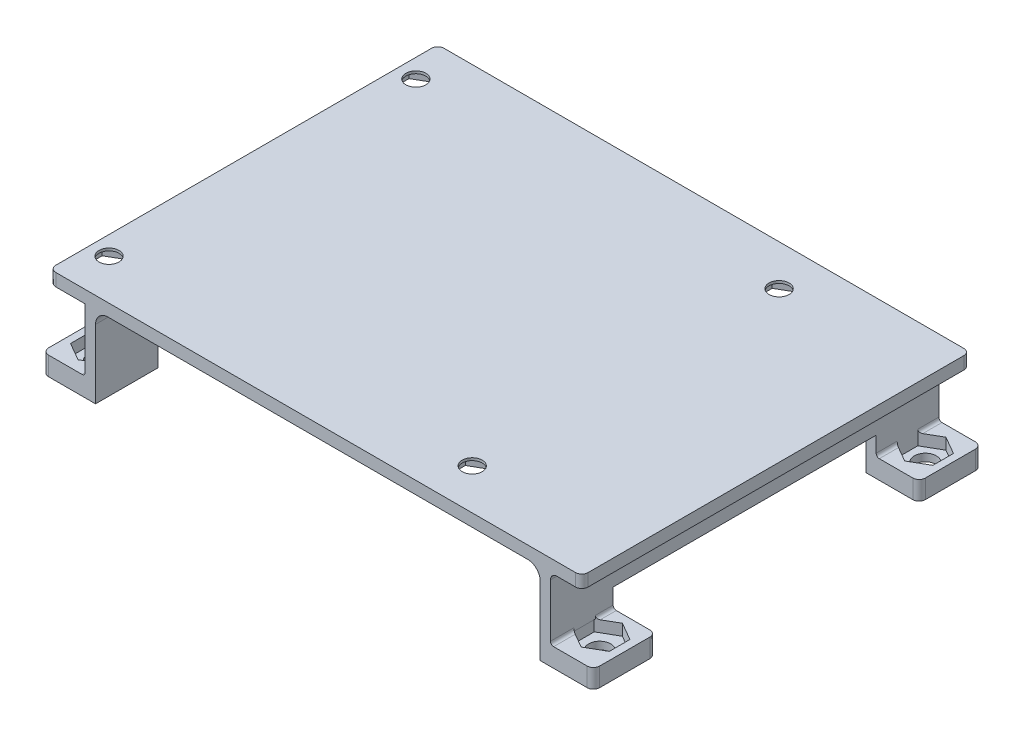
SolidWorks part; units mm, degrees
ref_plane "前基準面" through (0, 0, 0) normal (0, 0, 1) x (1, 0, 0)
ref_plane "上基準面" through (0, 0, 0) normal (0, 1, 0) x (1, 0, 0)
ref_plane "右基準面" through (0, 0, 0) normal (1, 0, 0) x (0, 0, -1)
sketch "草圖1" plane through (0, 0, 0) normal (0, 0, 1) x (1, 0, 0)
  line L0 (-133.4262, 0) -> (6537.8852, 0) construction
  line L1 (0, -133.4262) -> (0, 6537.8852) construction
  line L2 (-44, 0) -> (-44, 3)
  line L3 (-44, 3) -> (-37.15, 3)
  line L4 (-37.15, 3) -> (-37.15, 13)
  line L6 (37.15, 13) -> (37.15, 3)
  line L7 (37.15, 3) -> (44, 3)
  line L8 (44, 3) -> (44, 0)
  line L10 (-35.5, 0) -> (-35.5, 13)
  line L11 (-35.5, 13) -> (35.5, 13)
  line L12 (35.5, 13) -> (35.5, 0)
  line L13 (-44, 0) -> (-35.5, 0)
  line L14 (35.5, 0) -> (44, 0)
  line L16 (-42.85, 15) -> (-42.85, 13)
  line L17 (-37.15, 13) -> (-42.85, 13)
  line L18 (-42.85, 15) -> (42.15, 15)
  line L19 (42.15, 15) -> (42.15, 13)
  line L20 (42.15, 13) -> (37.15, 13)
  dimension "D1" = 1.65
  dimension "D2" = 13
  dimension "D3" = 71
  dimension "D4" = 88
  dimension "D5" = 2
  dimension "D6" = 3
  dimension "D7" = 85
  dimension "D8" = 5.7
extrude "填料-伸長1" add sketch "草圖1" along normal mid plane 62
sketch "草圖2" plane through (0, 0, 0) normal (1, 0, 0) x (0, 0, -1)
  line L0 (-1000, 0) -> (49000, 0) construction
  line L1 (0, -1000) -> (0, 49000) construction
  line L3 (-21, -6) -> (21, -6)
  line L4 (-21, -6) -> (-21, 6)
  line L5 (-21, 6) -> (21, 6)
  line L6 (21, -6) -> (21, 6)
  line L7 (-21, -6) -> (21, 6) construction
  line L8 (-21, 6) -> (21, -6) construction
  point P4 (0, 0)
  dimension "D1" = 42
  dimension "D2" = 12
extrude "除料-伸長1" cut sketch "草圖2" against normal through all both and the other way through all
sketch "草圖3" plane through (0, 0, 0) normal (0, 1, 0) x (1, 0, 0)
  line L0 (-40, -1017.5) -> (-40, 48982.5) construction
  line L2 (40, -1017.5) -> (40, 48982.5) construction
  line L4 (-1031.5, 26) -> (48968.5, 26) construction
  line L5 (0, -1000) -> (0, 49000) construction
  line L6 (-1031.5, -26) -> (48968.5, -26) construction
  line L8 (-1000, 0) -> (49000, 0) construction
  line L9 (-42.85, -31) -> (-37.15, -31) construction
  line L10 (35.5, -31) -> (44, -31) construction
  circle A0 centre (-40, 26) radius 1.75
  circle A1 centre (40, 26) radius 1.75
  circle A2 centre (40, -26) radius 1.75
  circle A3 centre (-40, -26) radius 1.75
  point P12 (-40, -31)
  point P16 (40, -31)
  dimension "D1" = 3.5
  dimension "D2" = 52
  dimension "D3" = 80
extrude "除料-伸長3" cut sketch "草圖3" along normal up to next contours A2 | A3 | A1 | A0
sketch "草圖5" plane through (0, 15, 0) normal (0, 1, 0) x (1, 0, 0)
  line L0 (-1000, 0) -> (49000, 0) construction
  line L1 (-1033.1907, 24.5) -> (48966.8093, 24.5) construction
  line L2 (-1033.1907, -24.5) -> (48966.8093, -24.5) construction
  line L3 (-39.85, 24.5) -> (-39.85, -24.5) construction
  line L4 (18.15, 24.5) -> (18.15, -24.5) construction
  line L5 (-42.85, -31) -> (-42.85, 31) construction
  circle A0 centre (-39.85, 24.5) radius 1.6
  circle A1 centre (-39.85, -24.5) radius 1.6
  circle A2 centre (18.15, 24.5) radius 1.6
  circle A3 centre (18.15, -24.5) radius 1.6
  dimension "D3" = 3.2
  dimension "D1" = 49
  dimension "D2" = 24.5
  dimension "D4" = 58
  dimension "D5" = 3
extrude "除料-伸長5" cut sketch "草圖5" against normal blind 5
ref_plane "平面1" through (0, 3, 0) normal (0, 1, 0) x (1, 0, 0)
sketch "草圖17" plane through (0, 13, 0) normal (0, -1, 0) x (1, 0, 0)
  line L7 (20.75, 22.9989) -> (20.75, 26.0011)
  line L8 (20.75, 26.0011) -> (18.15, 27.5022)
  line L9 (18.15, 27.5022) -> (15.55, 26.0011)
  line L10 (15.55, 26.0011) -> (15.55, 22.9989)
  line L11 (15.55, 22.9989) -> (18.15, 21.4978)
  line L12 (18.15, 21.4978) -> (20.75, 22.9989)
  line L13 (20.75, -26.0011) -> (20.75, -22.9989)
  line L14 (20.75, -22.9989) -> (18.15, -21.4978)
  line L15 (18.15, -21.4978) -> (15.55, -22.9989)
  line L16 (15.55, -22.9989) -> (15.55, -26.0011)
  line L17 (15.55, -26.0011) -> (18.15, -27.5022)
  line L18 (18.15, -27.5022) -> (20.75, -26.0011)
  line L19 (-39.85, 21.4978) -> (-37.25, 22.9989)
  line L20 (-37.25, 22.9989) -> (-37.25, 26.0011)
  line L21 (-37.25, 26.0011) -> (-39.85, 27.5022)
  line L22 (-39.85, 27.5022) -> (-42.45, 26.0011)
  line L23 (-42.45, 26.0011) -> (-42.45, 22.9989)
  line L24 (-42.45, 22.9989) -> (-39.85, 21.4978)
  line L26 (-39.85, -27.5022) -> (-37.25, -26.0011)
  line L27 (-37.25, -26.0011) -> (-37.25, -22.9989)
  line L28 (-37.25, -22.9989) -> (-39.85, -21.4978)
  line L29 (-39.85, -21.4978) -> (-42.45, -22.9989)
  line L30 (-42.45, -22.9989) -> (-42.45, -26.0011)
  line L31 (-42.45, -26.0011) -> (-39.85, -27.5022)
  circle A0 centre (18.15, 24.5) radius 2.6 construction
  circle A1 centre (18.15, -24.5) radius 2.6 construction
  circle A2 centre (-39.85, 24.5) radius 2.6 construction
  circle A3 centre (-39.85, -24.5) radius 2.6 construction
  dimension "D1" = 5.2
  dimension "D2" = 5.2
  dimension "D3" = 5.2
  dimension "D4" = 5.2
extrude "除料-伸長8" cut sketch "草圖17" against normal blind 1.6 contours L13 L14 L15 L16 L17 L18 | L11 L12 L7 L8 L9 L10
fillet "圓角1" radius 1 12 edges at (42.15, 14, -31) (44, 1.5, -31) (44, 1.5, -21) (44, 1.5, 21) (44, 1.5, 31) (42.15, 14, 31) (-42.85, 14, -31) (-44, 1.5, -31) (-44, 1.5, -21) (-44, 1.5, 21) (-44, 1.5, 31) (-42.85, 14, 31)
fillet "圓角7" radius 2 2 edges at (35.5, 13, 0) (-35.5, 13, 0)
sketch "草圖19" plane through (0, 3, 0) normal (0, 1, 0) x (1, 0, 0)
  line L1 (-40, -29.2909) -> (-37.15, -27.6454)
  line L2 (-37.15, -27.6454) -> (-37.15, -24.3546)
  line L3 (-37.15, -24.3546) -> (-40, -22.7091)
  line L4 (-40, -22.7091) -> (-42.85, -24.3546)
  line L5 (-42.85, -24.3546) -> (-42.85, -27.6454)
  line L6 (-42.85, -27.6454) -> (-40, -29.2909)
  line L7 (39.8961, -28.8509) -> (42.7461, -27.2055)
  line L8 (42.7461, -27.2055) -> (42.7461, -23.9146)
  line L9 (42.7461, -23.9146) -> (39.8961, -22.2691)
  line L10 (39.8961, -22.2691) -> (37.0461, -23.9146)
  line L11 (37.0461, -23.9146) -> (37.0461, -27.2055)
  line L12 (37.0461, -27.2055) -> (39.8961, -28.8509)
  line L13 (42.85, 24.3546) -> (42.85, 27.6454)
  line L14 (42.85, 27.6454) -> (40, 29.2909)
  line L15 (40, 29.2909) -> (37.15, 27.6454)
  line L16 (37.15, 27.6454) -> (37.15, 24.3546)
  line L17 (37.15, 24.3546) -> (40, 22.7091)
  line L18 (40, 22.7091) -> (42.85, 24.3546)
  line L19 (-40, 22.7091) -> (-37.15, 24.3546)
  line L20 (-37.15, 24.3546) -> (-37.15, 27.6454)
  line L21 (-37.15, 27.6454) -> (-40, 29.2909)
  line L22 (-40, 29.2909) -> (-42.85, 27.6454)
  line L23 (-42.85, 27.6454) -> (-42.85, 24.3546)
  line L24 (-42.85, 24.3546) -> (-40, 22.7091)
  circle A0 centre (-40, -26) radius 2.85 construction
  circle A1 centre (39.8961, -25.56) radius 2.85 construction
  circle A2 centre (40, 26) radius 2.85 construction
  circle A3 centre (-40, 26) radius 2.85 construction
  dimension "D1" = 5.7
  dimension "D2" = 5.7
  dimension "D3" = 5.7
  dimension "D4" = 5.7
extrude "除料-伸長9" cut sketch "草圖19" against normal blind 1.8
fillet "圓角5" radius 0.5 8 edges at (37.15, 3, -22.6773) (37.15, 3, -29.3227) (37.15, 3, 29.1327) (37.15, 3, 22.4273) (-37.15, 3, -22.6773) (-37.15, 3, -29.3227) (-37.15, 3, 22.6773) (-37.15, 3, 29.3227)
fillet "圓角8" radius 1 1 edges at (37.15, 13, 0)
